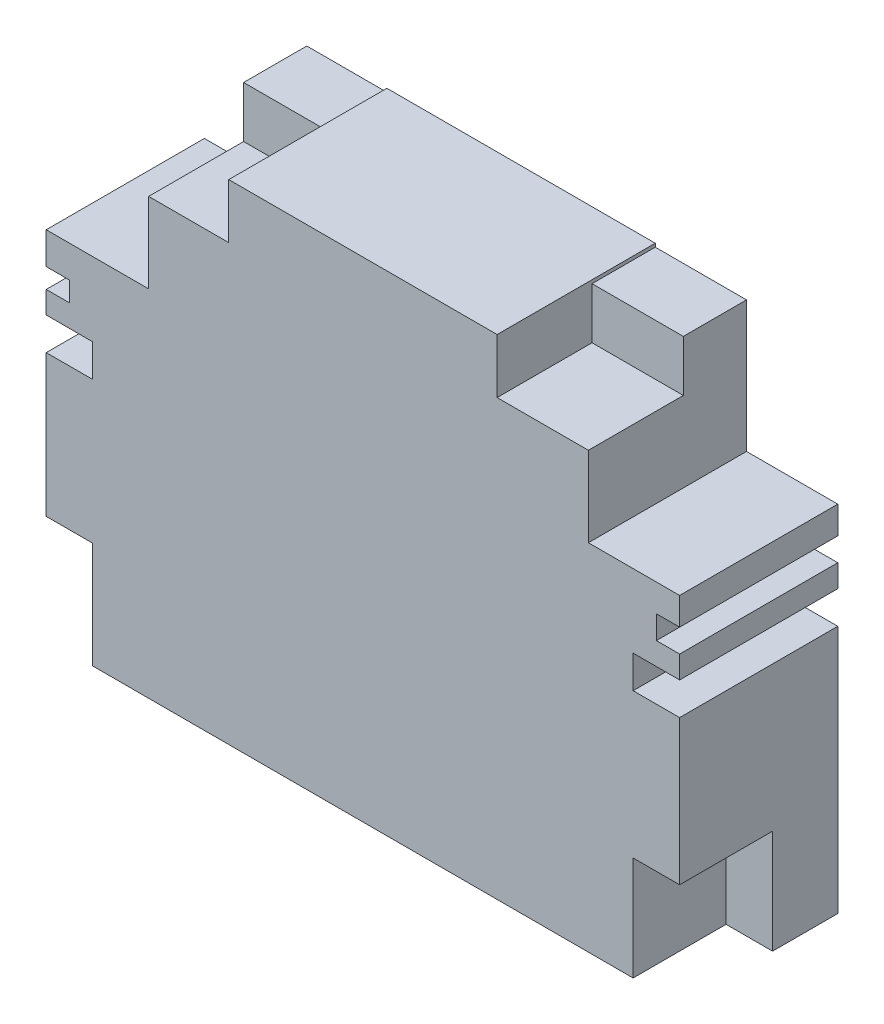
SolidWorks part; units mm, degrees
ref_plane "前视基准面" through (0, 0, 0) normal (0, 0, 1) x (1, 0, 0)
ref_plane "上视基准面" through (0, 0, 0) normal (0, 1, 0) x (1, 0, 0)
ref_plane "右视基准面" through (0, 0, 0) normal (1, 0, 0) x (0, 0, -1)
sketch "草图1" plane through (0, 0, 0) normal (0, 0, 1) x (1, 0, 0)
  line L1 (-78.2297, -37.126) -> (57.9503, -37.126)
  line L2 (-78.2297, -37.126) -> (-78.2297, 68.064)
  line L3 (-78.2297, 68.064) -> (57.9503, 68.064)
  line L4 (57.9503, -37.126) -> (57.9503, 68.064)
extrude "凸台-拉伸1" add sketch "草图1" along normal blind 34
sketch "草图3" plane through (0, 68.064, 0) normal (0, 1, 0) x (1, 0, 0)
  line L0 (57.9503, -34) -> (-78.2297, -34) construction
  line L1 (-78.2297, 0) -> (-38.9897, 0)
  line L2 (-78.2297, 0) -> (-78.2297, -34)
  line L3 (-78.2297, -34) -> (-38.9897, -34)
  line L4 (-38.9897, 0) -> (-38.9897, -34)
  line L6 (57.9503, 0) -> (18.7103, 0)
  line L7 (57.9503, 0) -> (57.9503, -34)
  line L8 (57.9503, -34) -> (18.7103, -34)
  line L9 (18.7103, 0) -> (18.7103, -34)
extrude "切除-拉伸1" cut sketch "草图3" against normal blind 28.96
sketch "草图4" plane through (0, 39.104, 0) normal (0, 1, 0) x (1, 0, 0)
  line L0 (-38.9897, 0) -> (-78.2297, 0) construction
  line L1 (-56.2097, 0) -> (-38.9897, 0)
  line L2 (-56.2097, 0) -> (-56.2097, -34)
  line L3 (-56.2097, -34) -> (-38.9897, -34)
  line L4 (-38.9897, 0) -> (-38.9897, -34)
  line L5 (-78.2297, -34) -> (-38.9897, -34) construction
  line L6 (-38.9897, -34) -> (-38.9897, 0) construction
extrude "凸台-拉伸2" add sketch "草图4" along normal blind 17.22
sketch "草图5" plane through (0, 39.104, 0) normal (0, 1, 0) x (1, 0, 0)
  line L0 (18.7103, -34) -> (57.9503, -34) construction
  line L1 (18.7103, 0) -> (38.3303, 0)
  line L2 (18.7103, 0) -> (18.7103, -34)
  line L3 (18.7103, -34) -> (38.3303, -34)
  line L4 (38.3303, 0) -> (38.3303, -34)
extrude "凸台-拉伸3" add sketch "草图5" along normal blind 17.22
sketch "草图6" plane through (-78.2297, 0, 0) normal (-1, 0, 0) x (0, 0, 1)
  line L0 (34, 39.104) -> (34, -37.126) construction
  line L1 (34, 32.2328) -> (0, 32.2328)
  line L2 (34, 32.2328) -> (34, 27.9928)
  line L3 (34, 27.9928) -> (0, 27.9928)
  line L4 (0, 32.2328) -> (0, 27.9928)
  line L5 (0, 39.104) -> (0, -37.126) construction
extrude "切除-拉伸2" cut sketch "草图6" against normal blind 5
sketch "草图7" plane through (-78.2297, 0, 0) normal (-1, 0, 0) x (0, 0, 1)
  line L0 (34, 27.9928) -> (34, -37.126) construction
  line L1 (34, 23.2283) -> (0, 23.2283)
  line L2 (34, 23.2283) -> (34, 16.2283)
  line L3 (34, 16.2283) -> (0, 16.2283)
  line L4 (0, 23.2283) -> (0, 16.2283)
  line L5 (0, 27.9928) -> (0, -37.126) construction
extrude "切除-拉伸4" cut sketch "草图7" against normal blind 10
sketch "草图9" plane through (0, 56.324, 0) normal (0, 1, 0) x (1, 0, 0)
  line L0 (18.7103, 0) -> (18.7103, -34) construction
  line L1 (38.3303, 0) -> (18.7103, 0)
  line L2 (38.3303, 0) -> (38.3303, -13.59)
  line L3 (38.3303, -13.59) -> (18.7103, -13.59)
  line L4 (18.7103, 0) -> (18.7103, -13.59)
extrude "凸台-拉伸4" add sketch "草图9" along normal blind 11
sketch "草图10" plane through (0, 56.324, 0) normal (0, 1, 0) x (1, 0, 0)
  line L0 (-38.9897, -34) -> (-38.9897, 0) construction
  line L1 (-56.2097, 0) -> (-38.9897, 0)
  line L2 (-56.2097, 0) -> (-56.2097, -13.58)
  line L3 (-56.2097, -13.58) -> (-38.9897, -13.58)
  line L4 (-38.9897, 0) -> (-38.9897, -13.58)
extrude "凸台-拉伸5" add sketch "草图10" along normal blind 11
sketch "草图11" plane through (57.9503, 0, 0) normal (1, 0, 0) x (0, 0, -1)
  line L0 (-34, -37.126) -> (-34, 39.104) construction
  line L1 (-34, 33.1959) -> (0, 33.1959)
  line L2 (-34, 33.1959) -> (-34, 28.1959)
  line L3 (-34, 28.1959) -> (0, 28.1959)
  line L4 (0, 33.1959) -> (0, 28.1959)
  line L5 (0, -37.126) -> (0, 39.104) construction
extrude "切除-拉伸7" cut sketch "草图11" against normal blind 5
sketch "草图13" plane through (57.9503, 0, 0) normal (1, 0, 0) x (0, 0, -1)
  line L1 (-33.7495, 23.3636) -> (0.0005, 23.3636)
  line L2 (-33.7495, 23.3636) -> (-33.7495, 16.3636)
  line L3 (-33.7495, 16.3636) -> (0.0005, 16.3636)
  line L4 (0.0005, 23.3636) -> (0.0005, 16.3636)
extrude "切除-拉伸9" cut sketch "草图13" against normal blind 10
sketch "草图15" plane through (0, 0, 33.7495) normal (0, 0, -1) x (-1, 0, 0)
  line L1 (-57.9503, 23.3636) -> (-47.9503, 23.3636)
  line L2 (-57.9503, 23.3636) -> (-57.9503, 16.3636)
  line L3 (-57.9503, 16.3636) -> (-47.9503, 16.3636)
  line L4 (-47.9503, 23.3636) -> (-47.9503, 16.3636)
extrude "切除-拉伸10" cut sketch "草图15" against normal blind 10
sketch "草图16" plane through (-78.2297, 0, 0) normal (-1, 0, 0) x (0, 0, 1)
  line L1 (34, -37.126) -> (12.4558, -37.126)
  line L2 (34, -37.126) -> (34, -14.2687)
  line L3 (34, -14.2687) -> (12.4558, -14.2687)
  line L4 (12.4558, -37.126) -> (12.4558, -14.2687)
extrude "切除-拉伸11" cut sketch "草图16" against normal blind 10
sketch "草图18" plane through (57.9503, 0, 0) normal (1, 0, 0) x (0, 0, -1)
  line L0 (-34, -37.126) -> (-34, 16.3636) construction
  line L1 (-34, -14.7731) -> (-14.0188, -14.7731)
  line L2 (-34, -14.7731) -> (-34, -37.126)
  line L3 (-34, -37.126) -> (-14.0188, -37.126)
  line L4 (-14.0188, -14.7731) -> (-14.0188, -37.126)
  line L5 (-34, -37.126) -> (0, -37.126) construction
extrude "切除-拉伸12" cut sketch "草图18" against normal blind 10
